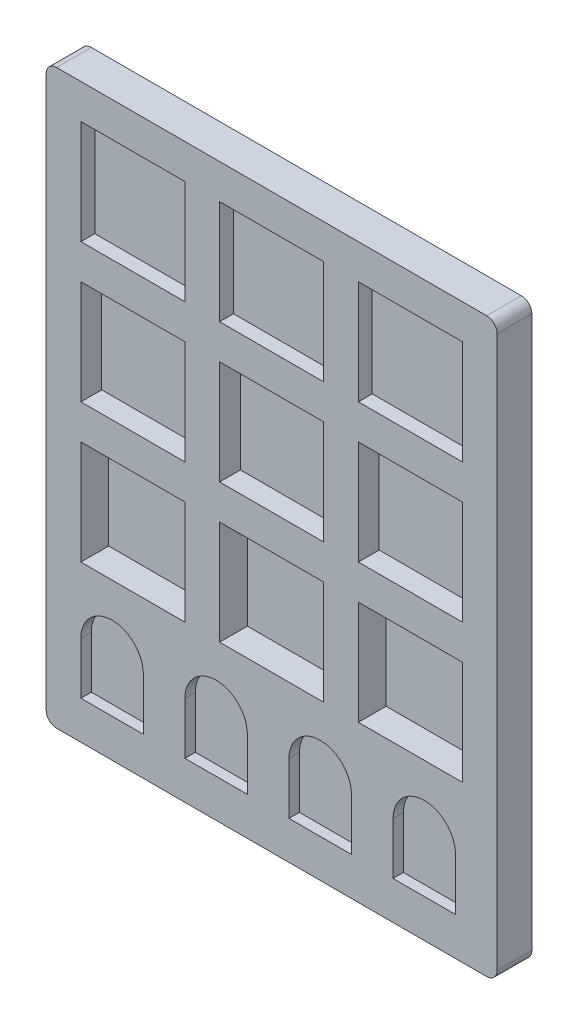
SolidWorks part; units mm, degrees
ref_plane "前视基准面" through (0, 0, 0) normal (0, 0, 1) x (1, 0, 0)
ref_plane "上视基准面" through (0, 0, 0) normal (0, 1, 0) x (1, 0, 0)
ref_plane "右视基准面" through (0, 0, 0) normal (1, 0, 0) x (0, 0, -1)
sketch "草图1" plane through (0, 0, 0) normal (0, 0, 1) x (1, 0, 0)
  line L1 (62, -82.5) -> (-62, -82.5)
  line L2 (65, -79.5) -> (65, 79.5)
  line L3 (62, 82.5) -> (-62, 82.5)
  line L4 (-65, -79.5) -> (-65, 79.5)
  line L5 (65, -82.5) -> (-65, 82.5) construction
  line L6 (65, 82.5) -> (-65, -82.5) construction
  arc A0 (-62, 82.5) -> (-65, 79.5) centre (-62, 79.5) ccw
  arc A1 (65, 79.5) -> (62, 82.5) centre (62, 79.5) ccw
  arc A2 (65, -79.5) -> (62, -82.5) centre (62, -79.5) cw
  arc A3 (-62, -82.5) -> (-65, -79.5) centre (-62, -79.5) cw
  point P0 (0, 0)
  dimension "D3" = 3
  dimension "D4" = 3
  dimension "D5" = 3
  dimension "D6" = 3
  dimension "D1" = 130
  dimension "D2" = 165
extrude "凸台-拉伸1" add sketch "草图1" along normal blind 10
sketch "草图6" plane through (0, 0, 10) normal (0, 0, 1) x (1, 0, 0)
  line L0 (62, 82.5) -> (-62, 82.5) construction
  line L1 (-55, 72.5) -> (-25, 72.5)
  line L2 (-55, 72.5) -> (-55, 42.5)
  line L3 (-55, 42.5) -> (-25, 42.5)
  line L4 (-25, 72.5) -> (-25, 42.5)
  line L5 (-55, 72.5) -> (-25, 42.5) construction
  line L6 (-55, 42.5) -> (-25, 72.5) construction
  line L7 (-65, 79.5) -> (-65, -79.5) construction
  line L8 (-15, 72.5) -> (-15, 42.5)
  line L9 (-15, 72.5) -> (15, 72.5)
  line L10 (15, 72.5) -> (15, 42.5)
  line L11 (-15, 42.5) -> (15, 42.5)
  line L12 (25, 72.5) -> (25, 42.5)
  line L13 (25, 72.5) -> (55, 72.5)
  line L14 (55, 72.5) -> (55, 42.5)
  line L15 (25, 42.5) -> (55, 42.5)
  point P0 (-40, 57.5)
  dimension "D1" = 10
  dimension "D2" = 10
  dimension "D3" = 30
  dimension "D4" = 30
  dimension "D5" = 3
extrude "切除-拉伸1" cut sketch "草图6" against normal blind 4
sketch "草图7" plane through (0, 0, 10) normal (0, 0, 1) x (1, 0, 0)
  line L0 (-55, 42.5) -> (-25, 42.5) construction
  line L1 (-25, 2.5) -> (-55, 2.5)
  line L2 (-25, 2.5) -> (-25, 32.5)
  line L3 (-25, 32.5) -> (-55, 32.5)
  line L4 (-55, 2.5) -> (-55, 32.5)
  line L5 (-25, 2.5) -> (-55, 32.5) construction
  line L6 (-25, 32.5) -> (-55, 2.5) construction
  line L7 (-65, 79.5) -> (-65, -79.5) construction
  line L8 (15, 2.5) -> (15, 32.5)
  line L9 (15, 2.5) -> (-15, 2.5)
  line L10 (-15, 2.5) -> (-15, 32.5)
  line L11 (15, 32.5) -> (-15, 32.5)
  line L12 (55, 2.5) -> (55, 32.5)
  line L13 (55, 2.5) -> (25, 2.5)
  line L14 (25, 2.5) -> (25, 32.5)
  line L15 (55, 32.5) -> (25, 32.5)
  point P0 (-40, 17.5)
  point P7 (-40, 42.5)
  point P10 (-55, 17.5)
  dimension "D1" = 10
  dimension "D2" = 10
  dimension "D3" = 30
  dimension "D4" = 30
  dimension "D5" = 3
extrude "切除-拉伸2" cut sketch "草图7" against normal blind 6
sketch "草图8" plane through (0, 0, 10) normal (0, 0, 1) x (1, 0, 0)
  line L0 (-55, 2.5) -> (-25, 2.5) construction
  line L1 (-25, -37.5) -> (-55, -37.5)
  line L2 (-25, -37.5) -> (-25, -7.5)
  line L3 (-25, -7.5) -> (-55, -7.5)
  line L4 (-55, -37.5) -> (-55, -7.5)
  line L5 (-25, -37.5) -> (-55, -7.5) construction
  line L6 (-25, -7.5) -> (-55, -37.5) construction
  line L7 (-65, 79.5) -> (-65, -79.5) construction
  line L8 (15, -37.5) -> (15, -7.5)
  line L9 (15, -37.5) -> (-15, -37.5)
  line L10 (-15, -37.5) -> (-15, -7.5)
  line L11 (15, -7.5) -> (-15, -7.5)
  line L12 (55, -37.5) -> (55, -7.5)
  line L13 (55, -37.5) -> (25, -37.5)
  line L14 (25, -37.5) -> (25, -7.5)
  line L15 (55, -7.5) -> (25, -7.5)
  point P0 (-40, -22.5)
  dimension "D1" = 10
  dimension "D2" = 10
  dimension "D3" = 30
  dimension "D4" = 30
  dimension "D5" = 3
extrude "切除-拉伸3" cut sketch "草图8" against normal blind 8
sketch "草图9" plane through (0, 0, 10) normal (0, 0, 1) x (1, 0, 0)
  line L5 (-55, -71.5) -> (-37, -71.5)
  line L6 (-37, -71.5) -> (-37, -56.5)
  line L8 (-55, -56.5) -> (-55, -71.5)
  line L9 (-55, -37.5) -> (-25, -37.5) construction
  line L10 (-65, 79.5) -> (-65, -79.5) construction
  line L11 (-25, -56.5) -> (-25, -71.5)
  line L12 (-25, -71.5) -> (-7, -71.5)
  line L13 (-7, -71.5) -> (-7, -56.5)
  line L14 (5, -56.5) -> (5, -71.5)
  line L15 (5, -71.5) -> (23, -71.5)
  line L16 (23, -71.5) -> (23, -56.5)
  line L17 (35, -56.5) -> (35, -71.5)
  line L18 (35, -71.5) -> (53, -71.5)
  line L19 (53, -71.5) -> (53, -56.5)
  arc A0 (-37, -56.5) -> (-55, -56.5) centre (-46, -56.5) ccw
  arc A1 (-7, -56.5) -> (-25, -56.5) centre (-16, -56.5) ccw
  arc A2 (23, -56.5) -> (5, -56.5) centre (14, -56.5) ccw
  arc A3 (53, -56.5) -> (35, -56.5) centre (44, -56.5) ccw
  dimension "D5" = 9
  dimension "D1" = 18
  dimension "D2" = 15
  dimension "D3" = 19
  dimension "D4" = 10
  dimension "D6" = 4
extrude "切除-拉伸4" cut sketch "草图9" against normal blind 3
